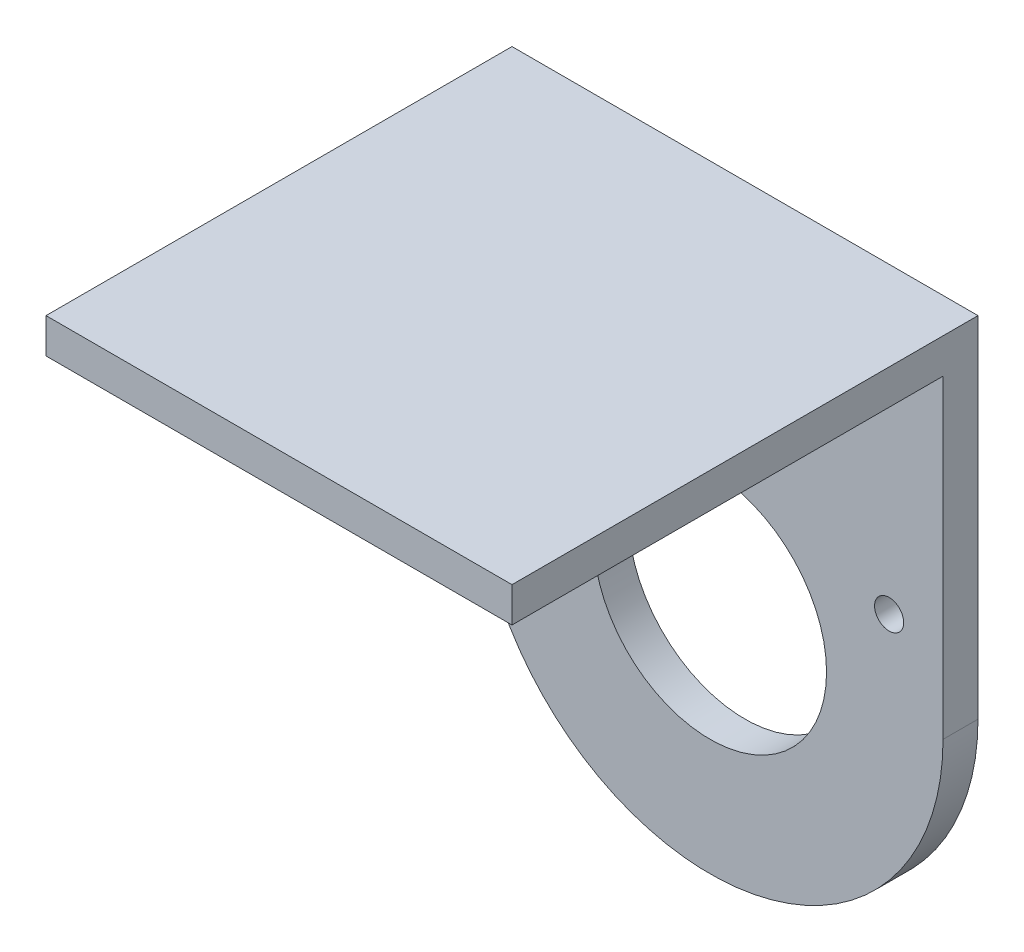
SolidWorks part; units mm, degrees
ref_plane "前视基准面" through (0, 0, 0) normal (0, 0, 1) x (1, 0, 0)
ref_plane "上视基准面" through (0, 0, 0) normal (0, 1, 0) x (1, 0, 0)
ref_plane "右视基准面" through (0, 0, 0) normal (1, 0, 0) x (0, 0, -1)
sketch "草图1" plane through (0, 0, 0) normal (0, 0, 1) x (1, 0, 0)
  line L1 (-17.553, 11.9527) -> (22.447, 11.9527)
  line L2 (-17.553, 11.9527) -> (-17.553, -18.0473)
  line L4 (22.447, 11.9527) -> (22.447, -18.0473)
  arc A0 (-17.553, -18.0473) -> (22.447, -18.0473) centre (2.447, -18.0473) ccw
  circle A1 centre (2.447, -18.0473) radius 10
  dimension "D3" = 20
  dimension "D1" = 40
  dimension "D2" = 30
extrude "凸台-拉伸2" add sketch "草图1" along normal blind 40
sketch "草图2" plane through (0, 0, 40) normal (0, 0, 1) x (1, 0, 0)
  line L0 (22.447, -18.0473) -> (22.447, 11.9527) construction
  line L2 (-17.553, -18.0473) -> (-17.553, 8.9527)
  line L3 (-17.553, 8.9527) -> (22.447, 8.9527)
  line L4 (22.447, -18.0473) -> (22.447, 8.9527)
  arc A0 (-17.553, -18.0473) -> (22.447, -18.0473) centre (2.447, -18.0473) ccw construction
  arc A1 (-17.553, -18.0473) -> (22.447, -18.0473) centre (2.447, -18.0473) ccw
  dimension "D1" = 27
extrude "切除-拉伸1" cut sketch "草图2" against normal blind 37
sketch "草图5" plane through (0, 0, 0) normal (0, 0, -1) x (-1, 0, 0)
  circle A0 centre (-10.0666, 2.3621) radius 1.25
  dimension "D1" = 2.5
extrude "切除-拉伸4" cut sketch "草图5" against normal blind 3
sketch "草图6" plane through (0, 0, 0) normal (0, 0, -1) x (-1, 0, 0)
  circle A0 centre (5.4334, 2.3621) radius 1.25
extrude "切除-拉伸5" cut sketch "草图6" against normal blind 3
sketch "草图7" plane through (0, 0, 0) normal (0, 0, -1) x (-1, 0, 0)
  circle A0 centre (-17.8166, -11.0613) radius 1.25
extrude "切除-拉伸6" cut sketch "草图7" against normal blind 3
sketch "草图8" plane through (0, 0, 0) normal (0, 0, -1) x (-1, 0, 0)
  circle A0 centre (13.1834, -11.0613) radius 1.25
extrude "切除-拉伸7" cut sketch "草图8" against normal blind 3
